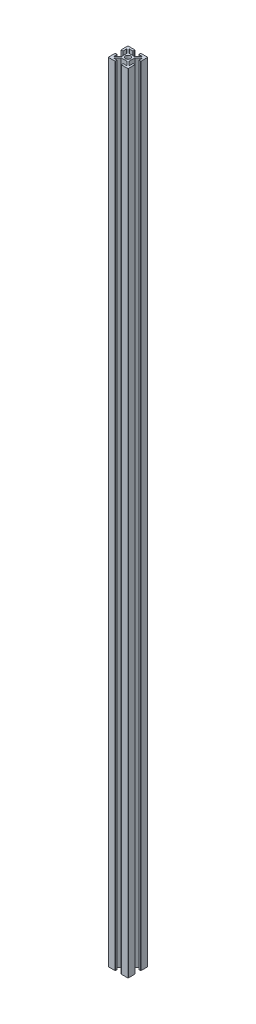
SolidWorks part; units mm, degrees
ref_plane "Front Plane" through (0, 0, 0) normal (0, 0, 1) x (1, 0, 0)
ref_plane "Top Plane" through (0, 0, 0) normal (0, 1, 0) x (1, 0, 0)
ref_plane "Right Plane" through (0, 0, 0) normal (1, 0, 0) x (0, 0, -1)
sketch "Sketch1" plane through (0, 0, 0) normal (0, 1, 0) x (1, 0, 0)
  line L0 (-9.8963, 3) -> (-8.1963, 3)
  line L3 (-3.1963, 10) -> (-9.6963, 10)
  line L4 (-10.0463, 3.15) -> (-10.0463, 9.65)
  line L7 (2.9332, 4) -> (-2.9332, 4)
  line L8 (-4, -2.9454) -> (-4, 2.9454)
  line L9 (-8.0463, 3.15) -> (-8.0463, 6.5862)
  line L10 (-6.6144, 8) -> (-3.1963, 8)
  line L11 (-3.0463, 8.15) -> (-3.0463, 9.85)
  line L12 (-8.0463, 8) -> (-4, 4) construction
  line L13 (-7.7908, 6.6929) -> (-4, 2.9454)
  line L14 (-6.7198, 7.7433) -> (-2.9332, 4)
  line L15 (8.0463, 8) -> (4, 4) construction
  line L22 (0, 0) -> (0, 11.6886) construction
  line L25 (0, 0) -> (-14.9841, 0) construction
  line L27 (6.7198, 7.7433) -> (2.9332, 4)
  line L28 (7.7908, 6.6929) -> (4, 2.9454)
  line L46 (3.0463, 8.15) -> (3.0463, 9.85)
  line L47 (6.6144, 8) -> (3.1963, 8)
  line L48 (8.0463, 3.15) -> (8.0463, 6.5862)
  line L49 (4, -2.9454) -> (4, 2.9454)
  line L50 (10.0463, 3.15) -> (10.0463, 9.65)
  line L51 (3.1963, 10) -> (9.6963, 10)
  line L52 (9.8963, 3) -> (8.1963, 3)
  line L53 (8.0463, -8) -> (4, -4) construction
  line L54 (-8.0463, -8) -> (-4, -4) construction
  line L55 (9.8963, -3) -> (8.1963, -3)
  line L56 (3.1963, -10) -> (9.6963, -10)
  line L57 (10.0463, -3.15) -> (10.0463, -9.65)
  line L58 (8.0463, -3.15) -> (8.0463, -6.5862)
  line L59 (6.6144, -8) -> (3.1963, -8)
  line L60 (3.0463, -8.15) -> (3.0463, -9.85)
  line L61 (7.7908, -6.6929) -> (4, -2.9454)
  line L62 (6.7198, -7.7433) -> (2.9332, -4)
  line L63 (-6.7198, -7.7433) -> (-2.9332, -4)
  line L64 (-7.7908, -6.6929) -> (-4, -2.9454)
  line L65 (-3.0463, -8.15) -> (-3.0463, -9.85)
  line L66 (-6.6144, -8) -> (-3.1963, -8)
  line L67 (-8.0463, -3.15) -> (-8.0463, -6.5862)
  line L68 (2.9332, -4) -> (-2.9332, -4)
  line L69 (-10.0463, -3.15) -> (-10.0463, -9.65)
  line L70 (-3.1963, -10) -> (-9.6963, -10)
  line L71 (-9.8963, -3) -> (-8.1963, -3)
  circle A0 centre (0, 0) radius 2.5
  arc A1 (-10.0463, 9.65) -> (-9.6963, 10) centre (-9.6963, 9.65) cw
  arc A2 (-9.8963, 3) -> (-10.0463, 3.15) centre (-9.8963, 3.15) cw
  arc A3 (-8.1963, 3) -> (-8.0463, 3.15) centre (-8.1963, 3.15) ccw
  arc A4 (-3.1963, 10) -> (-3.0463, 9.85) centre (-3.1963, 9.85) cw
  arc A5 (-3.1963, 8) -> (-3.0463, 8.15) centre (-3.1963, 8.15) ccw
  arc A6 (-6.7198, 7.7433) -> (-6.6144, 8) centre (-6.6144, 7.85) cw
  arc A7 (-7.7908, 6.6929) -> (-8.0463, 6.5862) centre (-7.8963, 6.5862) ccw
  arc A8 (7.7908, 6.6929) -> (8.0463, 6.5862) centre (7.8963, 6.5862) cw
  arc A9 (6.7198, 7.7433) -> (6.6144, 8) centre (6.6144, 7.85) ccw
  arc A10 (3.1963, 8) -> (3.0463, 8.15) centre (3.1963, 8.15) cw
  arc A11 (3.1963, 10) -> (3.0463, 9.85) centre (3.1963, 9.85) ccw
  arc A12 (8.1963, 3) -> (8.0463, 3.15) centre (8.1963, 3.15) cw
  arc A13 (9.8963, 3) -> (10.0463, 3.15) centre (9.8963, 3.15) ccw
  arc A14 (10.0463, 9.65) -> (9.6963, 10) centre (9.6963, 9.65) ccw
  arc A15 (10.0463, -9.65) -> (9.6963, -10) centre (9.6963, -9.65) cw
  arc A16 (9.8963, -3) -> (10.0463, -3.15) centre (9.8963, -3.15) cw
  arc A17 (8.1963, -3) -> (8.0463, -3.15) centre (8.1963, -3.15) ccw
  arc A18 (3.1963, -10) -> (3.0463, -9.85) centre (3.1963, -9.85) cw
  arc A19 (3.1963, -8) -> (3.0463, -8.15) centre (3.1963, -8.15) ccw
  arc A20 (6.7198, -7.7433) -> (6.6144, -8) centre (6.6144, -7.85) cw
  arc A21 (7.7908, -6.6929) -> (8.0463, -6.5862) centre (7.8963, -6.5862) ccw
  arc A22 (-7.7908, -6.6929) -> (-8.0463, -6.5862) centre (-7.8963, -6.5862) cw
  arc A23 (-6.7198, -7.7433) -> (-6.6144, -8) centre (-6.6144, -7.85) ccw
  arc A24 (-3.1963, -8) -> (-3.0463, -8.15) centre (-3.1963, -8.15) cw
  arc A25 (-3.1963, -10) -> (-3.0463, -9.85) centre (-3.1963, -9.85) ccw
  arc A26 (-8.1963, -3) -> (-8.0463, -3.15) centre (-8.1963, -3.15) cw
  arc A27 (-9.8963, -3) -> (-10.0463, -3.15) centre (-9.8963, -3.15) ccw
  arc A28 (-10.0463, -9.65) -> (-9.6963, -10) centre (-9.6963, -9.65) ccw
  point P8 (-10.0463, 10)
  point P27 (-10.0463, 3)
  point P30 (3.0463, 8)
  point P31 (10.0463, -10)
  point P50 (4, 0)
  point P55 (-8.0463, 3)
  point P58 (-3.0463, 10)
  point P61 (-3.0463, 8)
  point P63 (0, 4)
  point P65 (3.0463, 10)
  point P66 (8.0463, 3)
  point P67 (10.0463, 3)
  point P68 (10.0463, 10)
  point P118 (-4, 0)
  point P119 (10.0463, -3)
  point P120 (8.0463, -3)
  point P121 (3.0463, -10)
  point P122 (0, -4)
  point P123 (-3.0463, -8)
  point P124 (-3.0463, -10)
  point P125 (-8.0463, -3)
  point P126 (3.0463, -8)
  point P127 (-10.0463, -3)
  point P128 (-10.0463, -10)
  dimension "D2" = 0.35
  dimension "D3" = 0.15
  dimension "D4" = 0.15
  dimension "D5" = 0.15
  dimension "D12" = 0.15
  dimension "D13" = 0.15
  dimension "D14" = 0.15
  dimension "D6" = 2
  dimension "D7" = 7
  dimension "D8" = 7
  dimension "D9" = 2
  dimension "D10" = 0.75
  dimension "D11" = 0.75
extrude "Boss-Extrude2" add sketch "Sketch1" along normal blind 800
